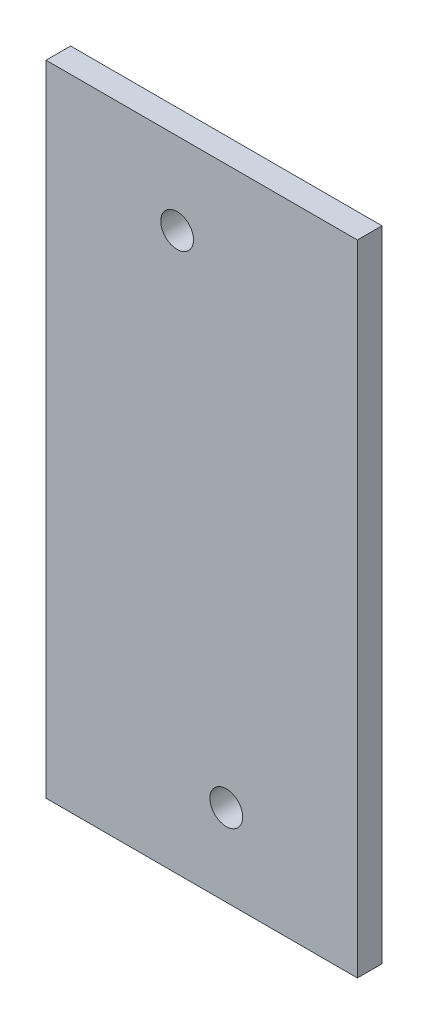
SolidWorks part; units mm, degrees
ref_plane "Plan de face" through (0, 0, 0) normal (0, 0, 1) x (1, 0, 0)
ref_plane "Plan de dessus" through (0, 0, 0) normal (0, 1, 0) x (1, 0, 0)
ref_plane "Plan de droite" through (0, 0, 0) normal (1, 0, 0) x (0, 0, -1)
sketch "Esquisse1" plane through (0, 0, 0) normal (0, 0, 1) x (1, 0, 0)
  line L0 (0, 0) -> (95, 0) construction
  line L1 (0, 0) -> (57, 0) construction
  line L2 (57, 0) -> (57, 165) construction
  line L3 (57, 165) -> (95, 165)
  line L4 (95, 165) -> (95, -155)
  line L5 (95, -155) -> (57, -155)
  line L7 (57, 165) -> (57, -155)
  dimension "D1" = 165
  dimension "D2" = 95
  dimension "D3" = 38
  dimension "D4" = 320
  dimension "D5" = 320
extrude "Boss.-Extru.1" add sketch "Esquisse1" along normal blind 3
sketch "Esquisse2" plane through (0, 0, 3) normal (0, 0, 1) x (1, 0, 0)
  line L2 (95, 165) -> (73, 165) construction
  line L3 (95, 165) -> (57, 165) construction
  line L4 (73, 165) -> (73, 155) construction
  line L5 (73, 155) -> (73, 97) construction
  line L6 (73, 97) -> (79, 97) construction
  circle A1 centre (73, 155) radius 2
  circle A2 centre (79, 97) radius 2
  dimension "D5" = 58
  dimension "D3" = 10
  dimension "D4" = 22
  dimension "D6" = 6
extrude "Enlèv. mat.-Extru.1" cut sketch "Esquisse2" against normal up to next
sketch "Esquisse3" plane through (0, 0, 3) normal (0, 0, 1) x (1, 0, 0)
  line L0 (57, -155) -> (57, 87)
  line L1 (57, 165) -> (57, -155) construction
  line L2 (57, 87) -> (95, 87)
  line L3 (95, -155) -> (95, 165) construction
  line L4 (95, 87) -> (95, -155)
  line L5 (95, -155) -> (57, -155)
extrude "Enlèv. mat.-Extru.2" cut sketch "Esquisse3" against normal up to next
